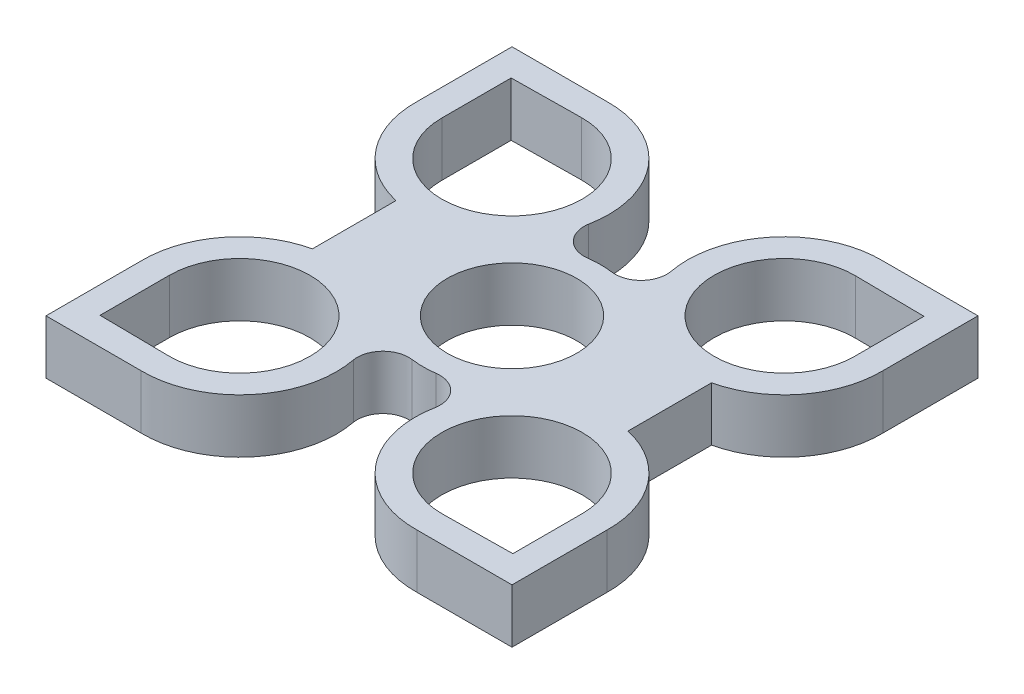
SolidWorks part; units mm, degrees
ref_plane "Front Plane" through (0, 0, 0) normal (0, 0, 1) x (1, 0, 0)
ref_plane "Top Plane" through (0, 0, 0) normal (0, 1, 0) x (1, 0, 0)
ref_plane "Right Plane" through (0, 0, 0) normal (1, 0, 0) x (0, 0, -1)
sketch "Sketch1" plane through (0, 0, 0) normal (0, 1, 0) x (1, 0, 0)
  line L0 (-78.3475, 0) -> (78.3475, 0) construction
  line L1 (0, -63.4598) -> (0, 63.4598) construction
  line L2 (-107.8, 107.8) -> (-107.8, 63.8)
  line L3 (-107.8, 107.8) -> (-62.8, 107.8)
  line L5 (-95.5, 95.1) -> (-63.4025, 95.4975)
  line L6 (-95.5, 95.1) -> (-95.5, 63)
  line L7 (-73, 19.3303) -> (-73, -19.3303)
  line L8 (73, 19.3303) -> (73, -19.3303)
  line L9 (95.5, 95.1) -> (95.5, 63)
  line L10 (95.5, 95.1) -> (63.4025, 95.4975)
  line L11 (107.8, 107.8) -> (62.8, 107.8)
  line L12 (107.8, 107.8) -> (107.8, 63.8)
  line L13 (107.8, -107.8) -> (107.8, -63.8)
  line L14 (107.8, -107.8) -> (62.8, -107.8)
  line L15 (95.5, -95.1) -> (63.4025, -95.4975)
  line L16 (95.5, -95.1) -> (95.5, -63)
  line L17 (-95.5, -95.1) -> (-95.5, -63)
  line L18 (-95.5, -95.1) -> (-63.4025, -95.4975)
  line L19 (-107.8, -107.8) -> (-62.8, -107.8)
  line L20 (-107.8, -107.8) -> (-107.8, -63.8)
  circle A0 centre (0, 0) radius 30
  arc A1 (-5.5518, -40.6224) -> (5.5518, -40.6224) centre (0, 0) ccw
  arc A3 (-95.5, 63) -> (-63.4025, 95.4975) centre (-63, 63) ccw
  arc A4 (-18.9704, 54.7277) -> (-5.5518, 40.6224) centre (-7.1767, 52.5119) ccw
  arc A5 (-107.8, 63.8) -> (-73, 19.323) centre (-63, 63) ccw
  arc A6 (-94.2454, 95.1155) -> (-95.5, 93.8453) centre (-63, 63) ccw
  arc A7 (94.2454, 95.1155) -> (95.5, 93.8453) centre (63, 63) cw
  arc A8 (107.8, 63.8) -> (73, 19.323) centre (63, 63) cw
  arc A9 (18.9704, 54.7277) -> (5.5518, 40.6224) centre (7.1767, 52.5119) cw
  arc A10 (95.5, 63) -> (63.4025, 95.4975) centre (63, 63) cw
  arc A11 (95.5, -63) -> (63.4025, -95.4975) centre (63, -63) ccw
  arc A12 (18.9704, -54.7277) -> (5.5518, -40.6224) centre (7.1767, -52.5119) ccw
  arc A13 (107.8, -63.8) -> (73, -19.323) centre (63, -63) ccw
  arc A14 (94.2454, -95.1155) -> (95.5, -93.8453) centre (63, -63) ccw
  arc A15 (-94.2454, -95.1155) -> (-95.5, -93.8453) centre (-63, -63) cw
  arc A16 (-107.8, -63.8) -> (-73, -19.323) centre (-63, -63) cw
  arc A17 (-18.9704, -54.7277) -> (-5.5518, -40.6224) centre (-7.1767, -52.5119) cw
  arc A18 (-95.5, -63) -> (-63.4025, -95.4975) centre (-63, -63) cw
  arc A19 (5.5518, 40.6224) -> (-5.5518, 40.6224) centre (0, 0) ccw
  arc A20 (-19.0327, 54.3653) -> (-63.8, 107.8) centre (-63, 63) ccw
  arc A21 (19.0327, -54.3653) -> (63.8, -107.8) centre (63, -63) ccw
  arc A22 (-19.0327, -54.3653) -> (-63.8, -107.8) centre (-63, -63) cw
  arc A23 (19.0327, 54.3653) -> (63.8, 107.8) centre (63, 63) cw
  point P4 (-63, 63)
  point P8 (0, 0)
  point P11 (0, 0)
  point P43 (63, 63)
  point P70 (63, -63)
  point P71 (-63, -63)
  point P73 (-73, 0)
  point P74 (73, 0)
  dimension "D1" = 60
  dimension "D2" = 82
  dimension "D5" = 65
  dimension "D6" = 89.6143
  dimension "D11" = 12
  dimension "D3" = 63
  dimension "D4" = 63
  dimension "D7" = 45
  dimension "D8" = 44
  dimension "D9" = 32.0975
  dimension "D10" = 32.1
  dimension "D12" = 73
extrude "Boss-Extrude1" add sketch "Sketch1" along normal blind 25
